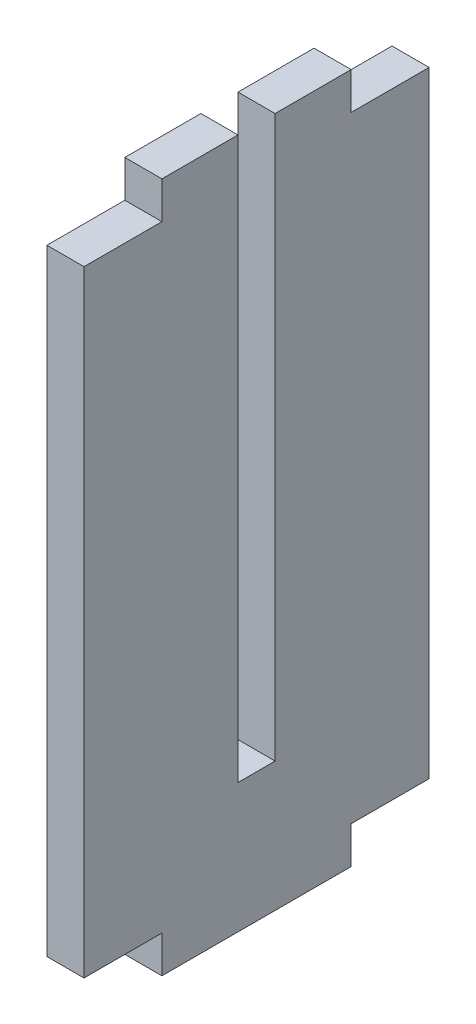
SolidWorks part; units mm, degrees
ref_plane "Front Plane" through (0, 0, 0) normal (0, 0, 1) x (1, 0, 0)
ref_plane "Top Plane" through (0, 0, 0) normal (0, 1, 0) x (1, 0, 0)
ref_plane "Right Plane" through (0, 0, 0) normal (1, 0, 0) x (0, 0, -1)
sketch "Sketch1" plane through (0, 0, 0) normal (1, 0, 0) x (0, 0, -1)
  line L1 (0, 0) -> (50.8, 0)
  line L2 (0, 0) -> (0, 101.6)
  line L3 (0, 101.6) -> (50.8, 101.6)
  line L4 (50.8, 0) -> (50.8, 101.6)
  line L5 (25.4, 101.6) -> (25.4, 0) construction
  line L6 (0, 50.8) -> (50.8, 50.8) construction
  point P112 (25.4, 50.8)
  dimension "D1" = 101.6
  dimension "D2" = 50.8
extrude "Boss-Extrude1" add sketch "Sketch1" along normal blind 5.461
sketch "Sketch2" plane through (5.461, 0, 0) normal (1, 0, 0) x (0, 0, -1)
  line L0 (25.4, 101.6) -> (25.4, 0) construction
  line L1 (50.8, 101.6) -> (0, 101.6) construction
  line L2 (0, 0) -> (50.8, 0) construction
  line L3 (0, 19.05) -> (50.8, 19.05) construction
  line L4 (0, 101.6) -> (0, 0) construction
  line L5 (50.8, 0) -> (50.8, 101.6) construction
  line L6 (39.3277, 101.6) -> (39.3277, 96.139)
  line L7 (22.6695, 101.6) -> (28.1305, 101.6)
  line L8 (22.6695, 101.6) -> (22.6695, 19.05)
  line L9 (22.6695, 19.05) -> (28.1305, 19.05)
  line L10 (28.1305, 101.6) -> (28.1305, 19.05)
  line L11 (25.4, 19.05) -> (25.4, 101.6) construction
  line L12 (22.6695, 60.325) -> (28.1305, 60.325) construction
  line L13 (0, 101.6) -> (11.4723, 101.6)
  line L14 (0, 101.6) -> (0, 96.139)
  line L15 (0, 96.139) -> (11.4723, 96.139)
  line L16 (11.4723, 101.6) -> (11.4723, 96.139)
  line L17 (5.7362, 96.139) -> (5.7362, 101.6) construction
  line L18 (0, 98.8695) -> (11.4723, 98.8695) construction
  line L19 (50.8, 96.139) -> (39.3277, 96.139)
  line L20 (50.8, 101.6) -> (50.8, 96.139)
  line L21 (50.8, 101.6) -> (39.3277, 101.6)
  line L22 (0, 50.8) -> (50.8, 50.8) construction
  line L23 (50.8, 0) -> (39.3277, 0)
  line L24 (50.8, 0) -> (50.8, 5.461)
  line L25 (50.8, 5.461) -> (39.3277, 5.461)
  line L26 (39.3277, 0) -> (39.3277, 5.461)
  line L27 (0, 2.7305) -> (11.4723, 2.7305) construction
  line L28 (5.7362, 5.461) -> (5.7362, 0) construction
  line L29 (11.4723, 0) -> (11.4723, 5.461)
  line L30 (0, 5.461) -> (11.4723, 5.461)
  line L31 (0, 0) -> (0, 5.461)
  line L32 (0, 0) -> (11.4723, 0)
  point P38 (5.7362, 2.7305)
  point P160 (5.7362, 98.8695)
  point P380 (25.4, 60.325)
  dimension "D1" = 19.05
  dimension "D2" = 5.461
  dimension "D3" = 5.461
  dimension "D4" = 11.4723
extrude "Cut-Extrude1" cut sketch "Sketch2" against normal blind 5.461
equation "\"Stock Thickness\" = .215in"
equation "\"D1@Boss-Extrude1\"=\"Stock Thickness\""
equation "\"Joint Length\"= .75in"
equation "\"D1@Sketch2\"=\"Joint Length\""
equation "\"D2@Sketch2\"=\"Stock Thickness\""
equation "\"D1@Cut-Extrude1\"=\"Stock Thickness\""
equation "\"D3@Sketch2\"=\"Stock Thickness\""
equation "\"D4@Sketch2\"=\"D2@Sketch1\"/3 - \"Stock Thickness\""
